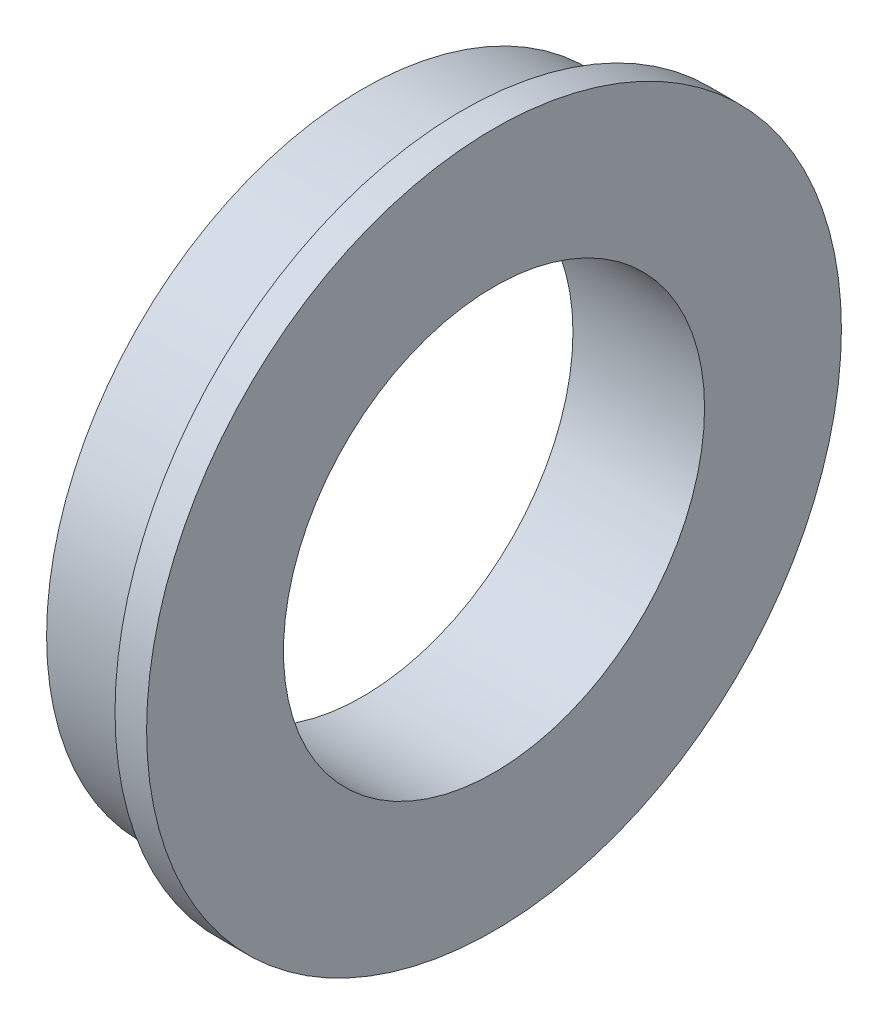
SolidWorks part; units mm, degrees
ref_plane "Front Plane" through (0, 0, 0) normal (0, 0, 1) x (1, 0, 0)
ref_plane "Top Plane" through (0, 0, 0) normal (0, 1, 0) x (1, 0, 0)
ref_plane "Right Plane" through (0, 0, 0) normal (1, 0, 0) x (0, 0, -1)
sketch "草图1" plane through (0, 0, 0) normal (1, 0, 0) x (0, 0, -1)
  circle A0 centre (0, 0) radius 4
  circle A1 centre (0, 0) radius 6.6
  dimension "D1" = 8
  dimension "D2" = 13.2
extrude "凸台-拉伸1" add sketch "草图1" along normal blind 2.5
sketch "草图2" plane through (0, 0, 0) normal (-1, 0, 0) x (0, 0, 1)
  circle A0 centre (0, 0) radius 6
  circle A1 centre (0, 0) radius 8.1125
  dimension "D1" = 12
extrude "切除-拉伸1" cut sketch "草图2" against normal blind 1.9
